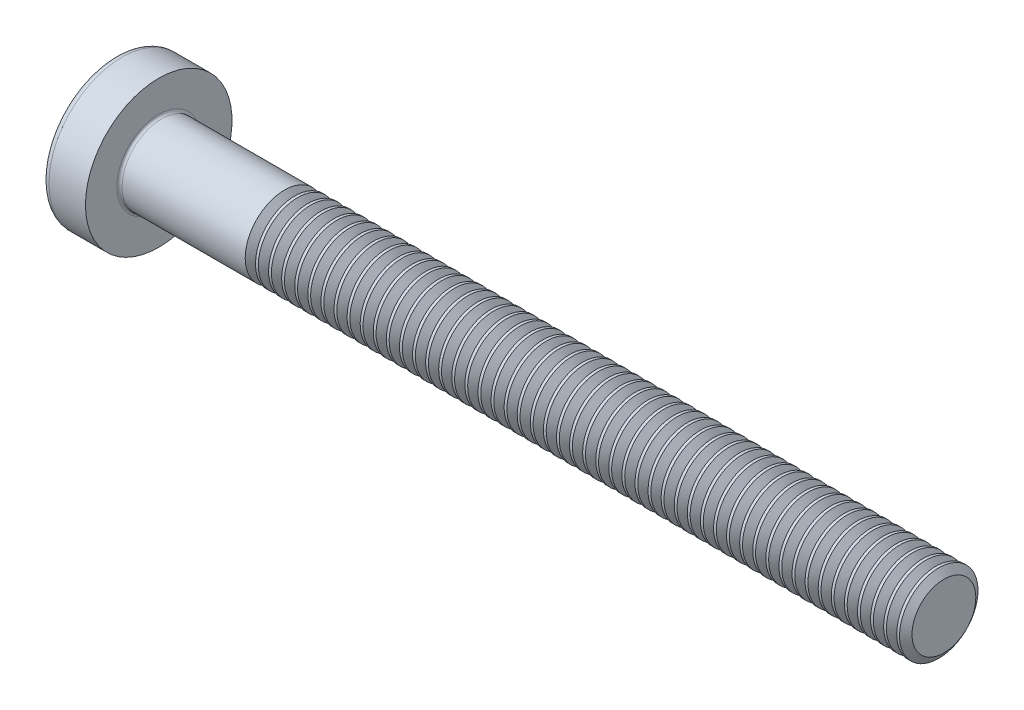
SolidWorks part; units mm, degrees
ref_plane "Plane1" through (0, 0, 0) normal (0, 0, 1) x (1, 0, 0)
ref_plane "Plane2" through (0, 0, 0) normal (0, 1, 0) x (1, 0, 0)
ref_plane "Plane3" through (0, 0, 0) normal (1, 0, 0) x (0, 0, -1)
sketch "BodySke" plane through (0, 0, 0) normal (0, 0, 1) x (1, 0, 0)
  line L0 (2.4, 1.5) -> (2.4, 2.8)
  line L1 (2.65, 6.35) -> (2.65, -3.175) construction
  line L2 (-25.4, 0) -> (127, 0) construction
  line L3 (32.4, 0) -> (0, 0)
  line L4 (2.4, 1.5) -> (32.4, 1.5)
  line L5 (32.4, 1.5) -> (32.4, 0)
  line L6 (1.0035, 2.8) -> (2.4, 2.8)
  line L8 (7.4, 6.35) -> (7.4, -3.175) construction
  arc A0 (0.7754, 2.6744) -> (0, 0) centre (5, 0) ccw
  arc A2 (0.7754, 2.6744) -> (1.0035, 2.8) centre (1.0035, 2.53) cw
  dimension "Head_crown_rad" = 5
  dimension "Head_fillet_rad" = 0.27
  dimension "Length" = 30
  dimension "Head_ht" = 2.4
  dimension "Head_dia" = 5.6
  dimension "Advance" = 0.5
  dimension "Thread_nom" = 25
  dimension "Diameter" = 3
revolve "Base-Revolve" add sketch "BodySke"
cosmetic thread "ThreadCosmetic" [suppressed]
fillet "Fillet1" radius 0.1 1 edges at (2.4, 0, 1.5)
sketch "Sketch3" plane through (0, 0, 0) normal (1, 0, 0) x (0, 0, -1)
  line L0 (0.37, -1.4) -> (-0.37, -1.4)
  line L1 (0.37, -1.4) -> (0.37, 1.4)
  line L2 (-0.37, 1.4) -> (0.37, 1.4)
  line L3 (-0.37, 1.4) -> (-0.37, -1.4)
  dimension "Cross_dia" = 2.8
  dimension "D1" = 1.4
  dimension "Cross_width" = 0.74
  dimension "D2" = 0.37
ref_plane "Plane4" through (1.75, 0, 0) normal (1, 0, 0) x (0, 0, -1)
sketch "Sketch4" plane through (1.75, 0, 0) normal (1, 0, 0) x (0, 0, -1)
  line L0 (0.37, -0.5275) -> (-0.37, -0.5275)
  line L1 (0.37, -0.5275) -> (0.37, 0.5275)
  line L2 (-0.37, 0.5275) -> (0.37, 0.5275)
  line L3 (-0.37, 0.5275) -> (-0.37, -0.5275)
  dimension "D1" = 0.74
  dimension "D2" = 1.055
  dimension "D3" = 0.37
  dimension "D4" = 0.5275
loft "Recess" cut profiles "Sketch3", "Sketch4"
pattern_circular "RecPat" count 2 every 90 about axis through (0, 0, 0) along (1, 0, 0) of "Recess"
sketch "RecCorSke" plane through (0, 0, 0) normal (0, 0, 1) x (1, 0, 0)
  line L0 (-3.175, 0) -> (15.875, 0) construction
  line L1 (-25.4, 0) -> (127, 0) construction
  line L2 (0, 0) -> (0, 0.6784)
  line L3 (0, 0.6784) -> (1.75, 0.556)
  line L4 (1.75, 0.556) -> (1.9307, 0)
  line L5 (1.9307, 0) -> (0, 0)
  dimension "Diameter" = 1.112
  dimension "Depth" = 1.75
  dimension "Draft_angle" = 4
  dimension "Bottom_angle" = 18
revolve "RecessCore" cut sketch "RecCorSke" angle 360 about L0
sketch "ThdSchSke" plane through (0, 0, 0) normal (0, 0, 1) x (1, 0, 0)
  line L0 (7.4, -1.2195) -> (7.2036, -1.5)
  line L1 (7.4, -1.2195) -> (7.5964, -1.5)
  line L2 (7.5964, -1.5) -> (7.5964, -1.875)
  line L3 (-3.175, 0) -> (5.1513, 0) construction
  line L5 (7.5964, -1.875) -> (7.2036, -1.875)
  line L6 (7.2036, -1.875) -> (7.2036, -1.5)
  dimension "Diameter" = 3
  dimension "SideAngle" = 55
  dimension "VeeAngle" = 70
  dimension "Thread_minor" = 2.439
  dimension "Overcut" = 3.75
  dimension "Start" = 7.4
revolve "ThreadSchematic" cut sketch "ThdSchSke" angle 360 about L3
pattern_linear "ThdSchPat" count 51 spacing 0.5 along (1, 0, 0) of "ThreadSchematic"
equation "\"D1@Sketch3\" = \"Cross_dia@Sketch3\" / 2"
equation "\"D2@Sketch3\" = \"Cross_width@Sketch3\" / 2"
equation "\"Depth@RecCorSke\" = \"Cross_depth@Plane4\""
equation "\"D1@Sketch4\" = \"Cross_width@Sketch3\""
equation "\"D2@Sketch4\" = \"Cross_dia@Sketch3\" - 2.0 * \"Cross_depth@Plane4\" * tan(26.5  * 0.017453292)"
equation "\"D3@Sketch4\" = \"D1@Sketch4\" / 2"
equation "\"D4@Sketch4\" = \"D2@Sketch4\" / 2"
equation "\"Thread_length@ThreadCosmetic\" = ((sgn( (\"Length@BodySke\" - \"Advance@BodySke\" * 2.0 ) - \"Thread_nom@BodySke\" )-1)*( (\"Length@BodySke\" - \"Advance@BodySke\" * 2.0 ) - \"Thread_nom@BodySke\" ))/-2+ \"Thread_nom@BodySke\""
equation "\"Thread_minor@ThdSchSke\" = \"Thread_minor@ThreadCosmetic\""
equation "\"Diameter@ThdSchSke\" = \"Diameter@BodySke\""
equation "\"Overcut@ThdSchSke\" = \"Diameter@BodySke\" * 1.25"
equation "\"Start@ThdSchSke\" = \"Head_ht@BodySke\" + \"Length@BodySke\" - \"Thread_length@ThreadCosmetic\"  '---Non-countersunk---"
equation "\"Num_threads@ThdSchPat\" = int( \"Thread_length@ThreadCosmetic\" / \"Advance@BodySke\" + 0.999 )  + 1"
equation "\"Advance@ThdSchPat\" = \"Thread_length@ThreadCosmetic\" /  (\"Num_threads@ThdSchPat\" - 1) 'relax it"
